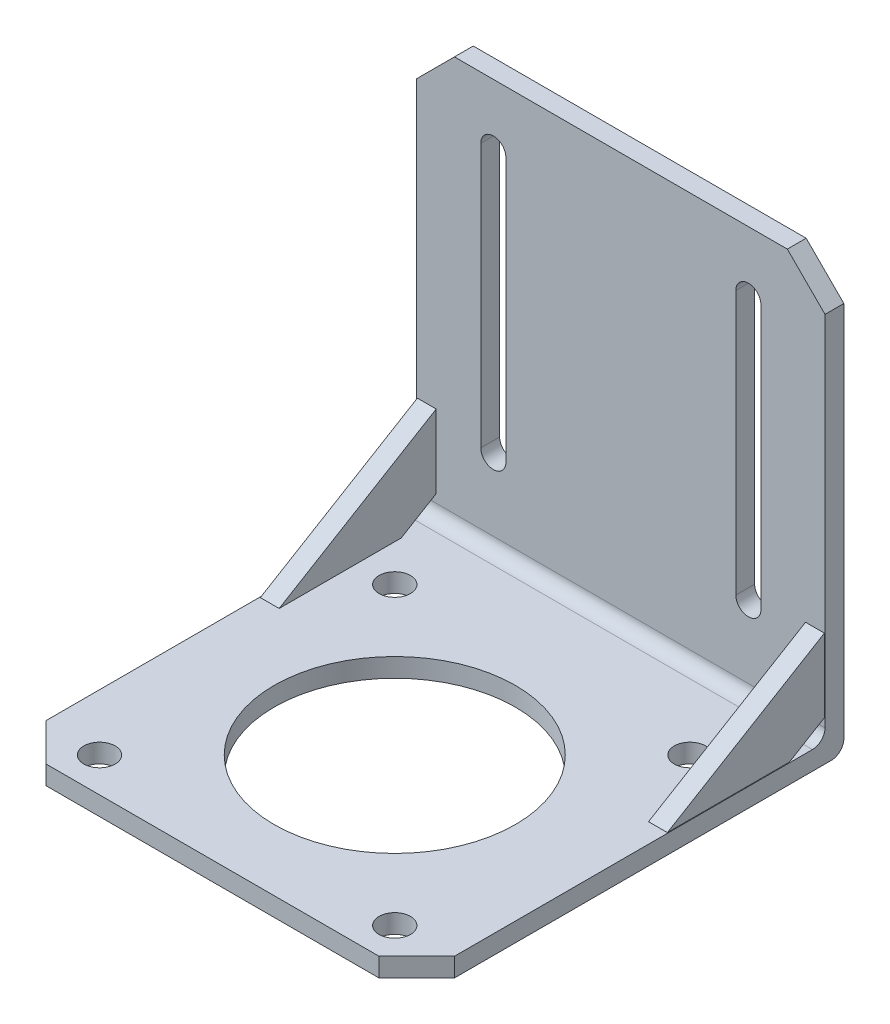
SolidWorks part; units mm, degrees
ref_plane "Front Plane" through (0, 0, 0) normal (0, 0, 1) x (1, 0, 0)
ref_plane "Top Plane" through (0, 0, 0) normal (0, 1, 0) x (1, 0, 0)
ref_plane "Right Plane" through (0, 0, 0) normal (1, 0, 0) x (0, 0, -1)
sketch "Sketch1" plane through (0, 0, 0) normal (0, 1, 0) x (1, 0, 0)
  line L1 (-32.5, 0) -> (32.5, 0)
  line L2 (-32.5, 0) -> (-32.5, 65)
  line L3 (-32.5, 65) -> (32.5, 65)
  line L4 (32.5, 0) -> (32.5, 65)
  dimension "D1" = 65
  dimension "D2" = 65
  dimension "D3" = 32.5
extrude "Boss-Extrude1" add sketch "Sketch1" along normal blind 3
sketch "Sketch2" plane through (0, 0, 0) normal (0, -1, 0) x (1, 0, 0)
  line L1 (-32.5, -65) -> (32.5, -65)
  line L2 (-32.5, -65) -> (-32.5, -68)
  line L3 (-32.5, -68) -> (32.5, -68)
  line L4 (32.5, -65) -> (32.5, -68)
  dimension "D1" = 3
extrude "Boss-Extrude2" add sketch "Sketch2" against normal blind 68
sketch "Sketch4" plane through (0, 3, 0) normal (0, 1, 0) x (1, 0, 0)
  line L0 (0, 0) -> (0, 65) construction
  line L1 (32.5, 65) -> (-32.5, 65) construction
  line L2 (-32.5, 0) -> (32.5, 0) construction
  circle A0 centre (0, 29) radius 19.2
  point P7 (0, 9.8)
  dimension "D1" = 38.4
  dimension "D2" = 9.8
extrude "Cut-Extrude1" cut sketch "Sketch4" against normal through all
sketch "Sketch5" plane through (0, 3, 0) normal (0, 1, 0) x (1, 0, 0)
  line L1 (-23.5, 52.5) -> (23.5, 52.5) construction
  line L2 (-23.5, 52.5) -> (-23.5, 5.5) construction
  line L3 (-23.5, 5.5) -> (23.5, 5.5) construction
  line L4 (23.5, 52.5) -> (23.5, 5.5) construction
  line L5 (-23.5, 52.5) -> (23.5, 5.5) construction
  line L6 (-23.5, 5.5) -> (23.5, 52.5) construction
  circle A0 centre (-23.5, 52.5) radius 2.5
  circle A1 centre (23.5, 52.5) radius 2.5
  circle A2 centre (23.5, 5.5) radius 2.5
  circle A3 centre (-23.5, 5.5) radius 2.5
  point P0 (0, 29)
  point P16 (0, 29)
  dimension "D2" = 5
  dimension "D1" = 47
  dimension "D3" = 4
extrude "Cut-Extrude2" cut sketch "Sketch5" against normal through all
sketch "Sketch6" plane through (0, 0, -65) normal (0, 0, 1) x (1, 0, 0)
  line L0 (0, 3) -> (0, 68) construction
  line L1 (-32.5, 3) -> (32.5, 3) construction
  line L2 (32.5, 68) -> (-32.5, 68) construction
  line L3 (-20.3, 58.2) -> (-20.3, 16.2) construction
  line L4 (-18.3, 58.2) -> (-18.3, 16.2)
  line L5 (-22.3, 58.2) -> (-22.3, 16.2)
  line L6 (-32.5, 68) -> (-32.5, 3) construction
  line L7 (20.3, 58.2) -> (20.3, 16.2) construction
  line L8 (18.3, 58.2) -> (18.3, 16.2)
  line L9 (22.3, 58.2) -> (22.3, 16.2)
  arc A0 (-18.3, 58.2) -> (-22.3, 58.2) centre (-20.3, 58.2) ccw
  arc A1 (-22.3, 16.2) -> (-18.3, 16.2) centre (-20.3, 16.2) ccw
  arc A2 (18.3, 58.2) -> (22.3, 58.2) centre (20.3, 58.2) cw
  arc A3 (22.3, 16.2) -> (18.3, 16.2) centre (20.3, 16.2) cw
  point P8 (-20.3, 37.2)
  point P13 (-20.3, 60.2)
  point P14 (-20.3, 14.2)
  point P17 (-32.5, 35.5)
  point P21 (20.3, 37.2)
  dimension "D1" = 2
  dimension "D2" = 46
  dimension "D3" = 10.2
  dimension "D4" = 7.8
extrude "Cut-Extrude3" cut sketch "Sketch6" against normal through all
sketch "Sketch8" plane through (-32.5, 0, 0) normal (-1, 0, 0) x (0, 0, 1)
  line L0 (-40, 3) -> (-65, 18)
  line L1 (-65, 3) -> (0, 3) construction
  line L2 (-65, 68) -> (-65, 3) construction
  line L3 (-65, 18) -> (-65, 6.3381)
  line L4 (-65, 6.3381) -> (-59.4365, 3)
  line L5 (-59.4365, 3) -> (-40, 3)
  dimension "D1" = 25
  dimension "D2" = 15
  dimension "D3" = 10
extrude "Boss-Extrude3" add sketch "Sketch8" against normal blind 3 from offset 0.1 offset against normal yes
sketch "Sketch9" plane through (32.5, 0, 0) normal (1, 0, 0) x (0, 0, -1)
  line L4 (40, 3) -> (59.4365, 3)
  line L5 (59.4365, 3) -> (65, 6.3381)
  line L6 (65, 6.3381) -> (65, 18)
  line L7 (65, 18) -> (40, 3)
  line L8 (40, 3) -> (59.4365, 3)
  line L9 (59.4365, 3) -> (65, 6.3381)
  line L10 (65, 6.3381) -> (65, 18)
  line L11 (65, 18) -> (40, 3)
  dimension "D1" = 0
extrude "Boss-Extrude4" add sketch "Sketch9" against normal blind 3 from offset 0.1 offset against normal yes
fillet "Fillet1" radius 2 2 edges at (0, 0, -68) (0, 3, -65)
chamfer "Chamfer1" distance 6 angle 45 4 edges at (-32.5, 68, -66.5) (32.5, 68, -66.5) (32.5, 1.5, 0) (-32.5, 1.5, 0)
